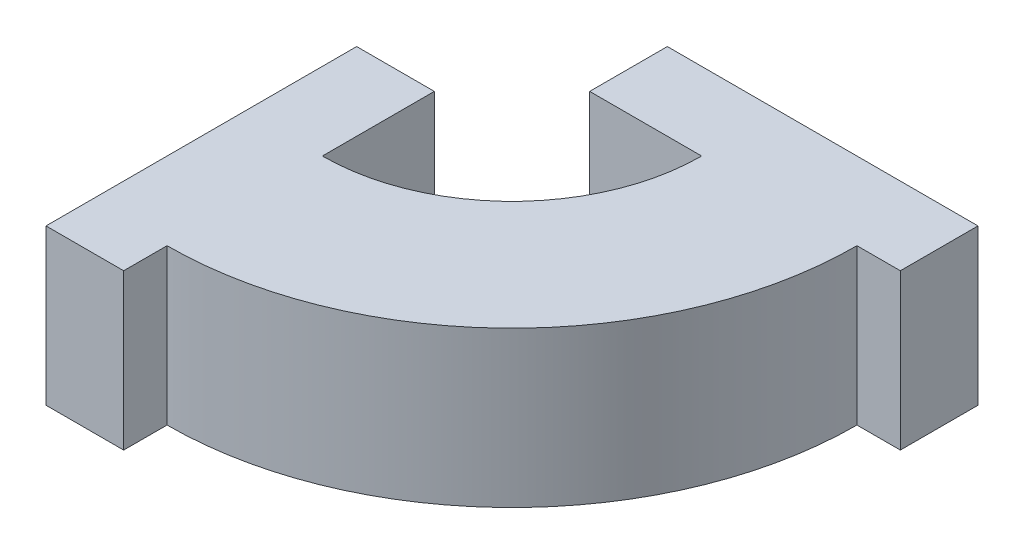
SolidWorks part; units mm, degrees
ref_plane "Front Plane" through (0, 0, 0) normal (0, 0, 1) x (1, 0, 0)
ref_plane "Top Plane" through (0, 0, 0) normal (0, 1, 0) x (1, 0, 0)
ref_plane "Right Plane" through (0, 0, 0) normal (1, 0, 0) x (0, 0, -1)
sketch "Sketch2" plane through (0, 0, 0) normal (0, 1, 0) x (1, 0, 0)
  line L0 (2, 0) -> (6, 0)
  line L1 (0, -2) -> (0, -6)
  line L2 (0, -2) -> (1, -2)
  line L4 (2, 0) -> (2, -1)
  line L6 (0, -6) -> (1, -6)
  line L8 (6, 0) -> (6, -1)
  line L9 (1, -2) -> (1, -6)
  line L10 (2, -1) -> (6, -1)
  arc A0 (1, -5.4417) -> (5.4417, -1) centre (1, -1) ccw
  arc A1 (1, -3.4417) -> (3.4417, -1) centre (1, -1) ccw
  dimension "D3" = 90
  dimension "D4" = 1
  dimension "D6" = 1
  dimension "D9" = 2
  dimension "D1" = 4
  dimension "D2" = 2
  dimension "D5" = 2
  dimension "D7" = 1
  dimension "D8" = 1
extrude "Boss-Extrude1" add sketch "Sketch2" along normal blind 2 contours L9 L2 L1 L6 | A1 L9 A0 L10 | L4 L10 L8 L0
